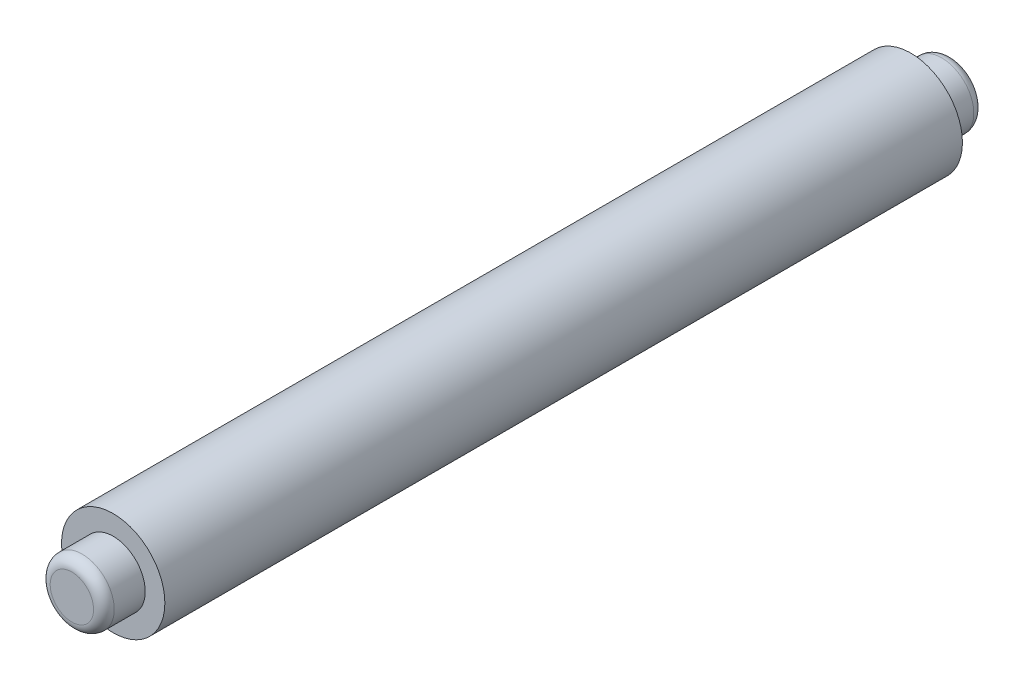
SolidWorks part; units mm, degrees
ref_plane "Front Plane" through (0, 0, 0) normal (0, 0, 1) x (1, 0, 0)
ref_plane "Top Plane" through (0, 0, 0) normal (0, 1, 0) x (1, 0, 0)
ref_plane "Right Plane" through (0, 0, 0) normal (1, 0, 0) x (0, 0, -1)
sketch "Sketch1" plane through (0, 0, 0) normal (0, 0, 1) x (1, 0, 0)
  circle A0 centre (-23.9727, -13.5789) radius 2.5
  dimension "D1" = 5
extrude "Boss-Extrude1" add sketch "Sketch1" along normal blind 38.61
sketch "Sketch2" plane through (0, 0, 38.61) normal (0, 0, 1) x (1, 0, 0)
  circle A0 centre (-23.9727, -13.5789) radius 1.55
  dimension "D1" = 3.1
extrude "Boss-Extrude2" add sketch "Sketch2" along normal blind 2
fillet "Fillet1" radius 0.5 1 edges at (-22.4227, -13.5789, 40.61)
sketch "Sketch3" plane through (0, 0, 0) normal (0, 0, -1) x (-1, 0, 0)
  circle A0 centre (23.9727, -13.5789) radius 1.55
  dimension "D1" = 3.1
extrude "Boss-Extrude3" add sketch "Sketch3" along normal blind 2
fillet "Fillet2" radius 0.5 1 edges at (-25.5227, -13.5789, -2)
